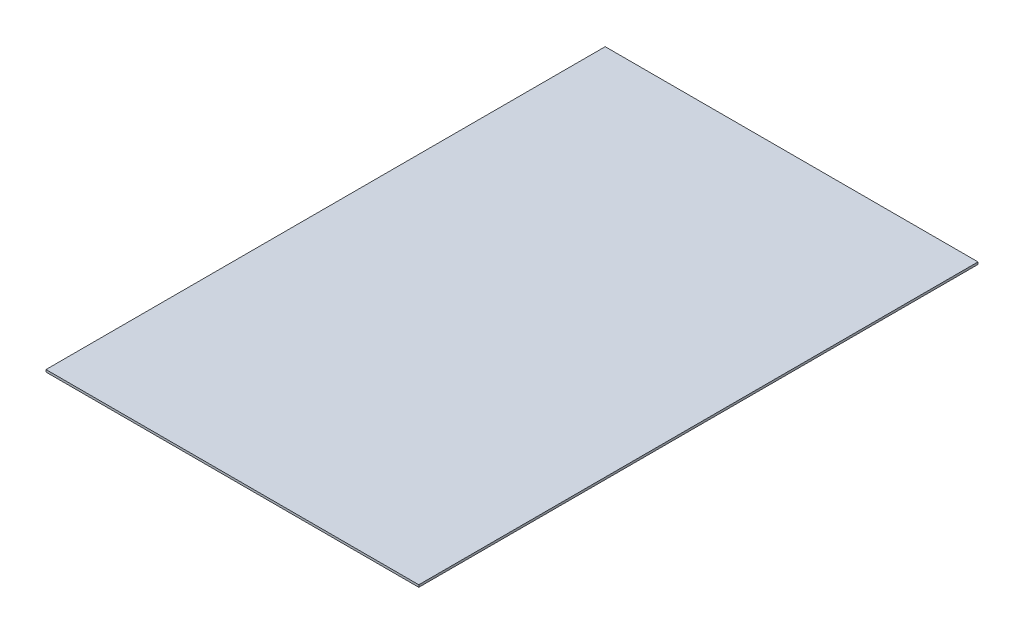
SolidWorks part; units mm, degrees
ref_plane "Front Plane" through (0, 0, 0) normal (0, 0, 1) x (1, 0, 0)
ref_plane "Top Plane" through (0, 0, 0) normal (0, 1, 0) x (1, 0, 0)
ref_plane "Right Plane" through (0, 0, 0) normal (1, 0, 0) x (0, 0, -1)
sketch "Sketch1" plane through (0, 0, 0) normal (0, 1, 0) x (1, 0, 0)
  line L1 (0, 0) -> (5000, 0)
  line L2 (0, 0) -> (0, 7500)
  line L3 (0, 7500) -> (5000, 7500)
  line L4 (5000, 0) -> (5000, 7500)
  dimension "D1" = 7500
  dimension "D2" = 5000
extrude "Boss-Extrude1" add sketch "Sketch1" along normal blind 30
